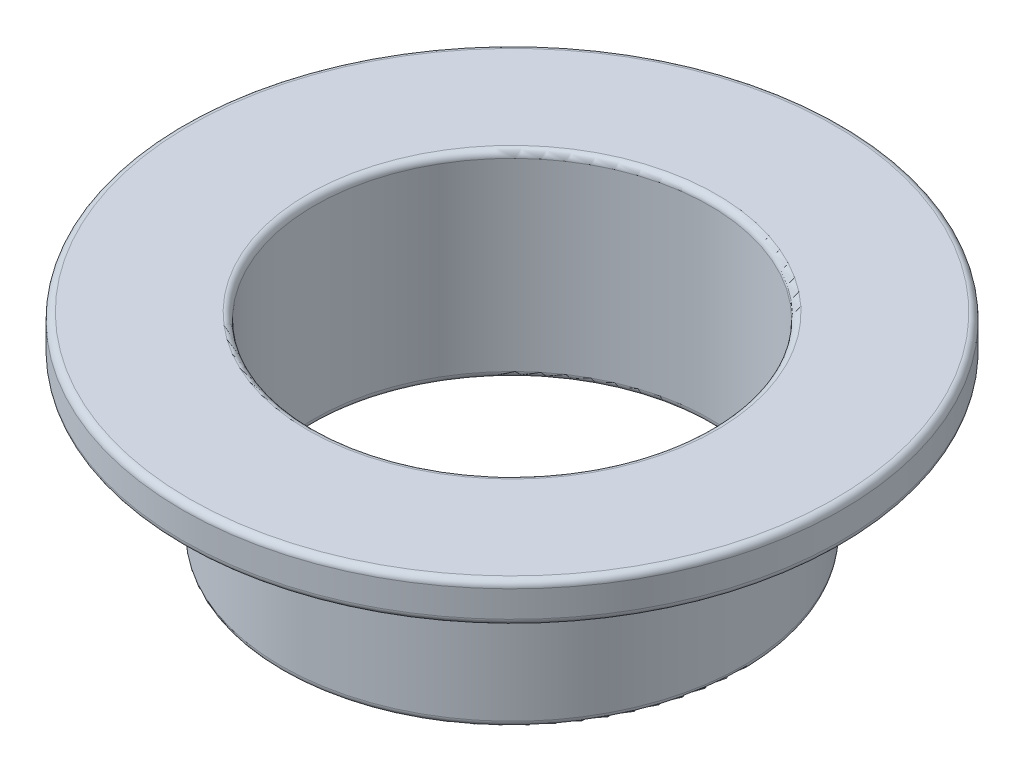
SolidWorks part; units mm, degrees
material "Brass"
ref_plane "Front Plane" through (0, 0, 0) normal (0, 0, 1) x (1, 0, 0)
ref_plane "Top Plane" through (0, 0, 0) normal (0, 1, 0) x (1, 0, 0)
ref_plane "Right Plane" through (0, 0, 0) normal (1, 0, 0) x (0, 0, -1)
sketch "Sketch1" plane through (0, 0, 0) normal (0, 1, 0) x (1, 0, 0)
  circle A0 centre (0, 0) radius 7
  circle A1 centre (0, 0) radius 6
  dimension "D1" = 14
  dimension "D2" = 12
extrude "Boss-Extrude1" add sketch "Sketch1" along normal blind 6
sketch "Sketch2" plane through (0, 6, 0) normal (0, 1, 0) x (1, 0, 0)
  circle A0 centre (0, 0) radius 6
  circle A1 centre (0, 0) radius 10
  dimension "D1" = 12
  dimension "D2" = 20
extrude "Boss-Extrude2" add sketch "Sketch2" against normal blind 1.2
fillet "Fillet1" radius 0.2 5 edges at (0, 6, 6) (0, 0, 6) (0, 0, 7) (0, 4.8, 10) (0, 6, 10)
